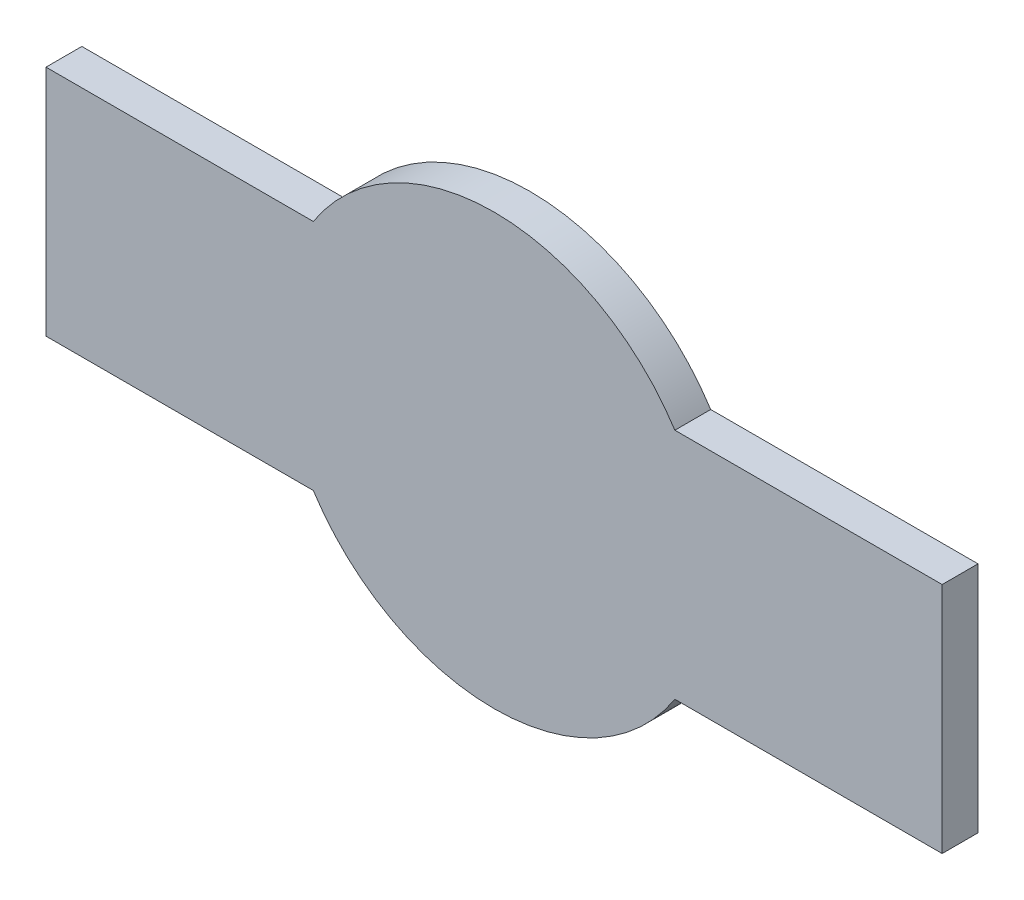
SolidWorks part; units mm, degrees
ref_plane "Plan de face" through (0, 0, 0) normal (0, 0, 1) x (1, 0, 0)
ref_plane "Plan de dessus" through (0, 0, 0) normal (0, 1, 0) x (1, 0, 0)
ref_plane "Plan de droite" through (0, 0, 0) normal (1, 0, 0) x (0, 0, -1)
sketch "Esquisse1" plane through (0, 0, 0) normal (0, 0, 1) x (1, 0, 0)
  line L1 (-125, -32.5) -> (125, -32.5)
  line L2 (-125, -32.5) -> (-125, 32.5)
  line L3 (-125, 32.5) -> (125, 32.5)
  line L4 (125, -32.5) -> (125, 32.5)
  line L5 (-125, -32.5) -> (125, 32.5) construction
  line L6 (-125, 32.5) -> (125, -32.5) construction
  circle A0 centre (0, 0) radius 60
  dimension "D3" = 120
  dimension "D1" = 250
  dimension "D2" = 65
extrude "Boss.-Extru.1" add sketch "Esquisse1" along normal blind 10 contours A0 | L2 L1 L4 L3
